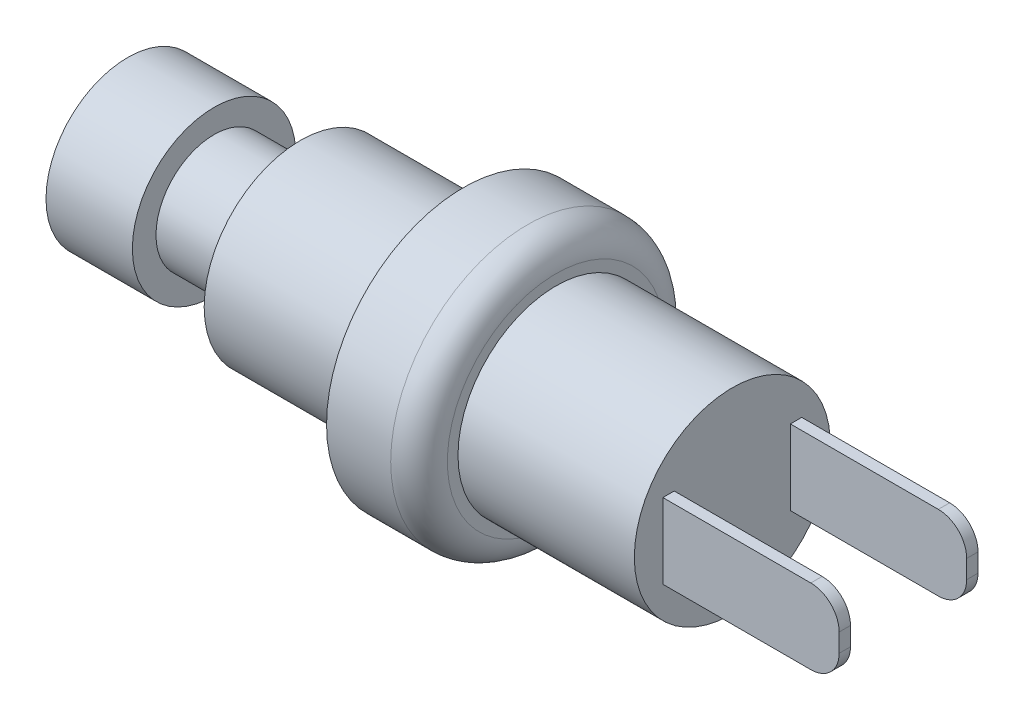
SolidWorks part; units mm, degrees
ref_plane "Front Plane" through (0, 0, 0) normal (0, 0, 1) x (1, 0, 0)
ref_plane "Top Plane" through (0, 0, 0) normal (0, 1, 0) x (1, 0, 0)
ref_plane "Right Plane" through (0, 0, 0) normal (1, 0, 0) x (0, 0, -1)
sketch "Sketch1" plane through (0, 0, 0) normal (0, 0, 1) x (1, 0, 0)
  line L0 (0, 0) -> (23.4906, 0) construction
  line L1 (3.7675, 0) -> (3.7675, 2.883)
  line L2 (3.7675, 2.883) -> (6.8155, 2.883)
  line L3 (6.8155, 2.883) -> (6.8155, 2.05)
  line L4 (6.8155, 2.05) -> (9.8635, 2.05)
  line L5 (9.8635, 2.05) -> (9.8635, 3.397)
  line L6 (9.8635, 3.397) -> (15.6165, 3.397)
  line L7 (15.6165, 3.397) -> (15.6165, 4.832)
  line L8 (15.6165, 4.832) -> (18.8805, 4.832)
  line L9 (18.8805, 4.832) -> (18.8805, 3.4579)
  line L10 (18.8805, 3.4579) -> (25.1035, 3.4579)
  line L11 (25.1035, 3.4579) -> (25.1035, 0)
  line L12 (25.1035, 0) -> (3.7675, 0)
  point P15 (9.8635, 2.7235)
  dimension "D1" = 6.096
  dimension "D2" = 2.883
  dimension "D3" = 5.753
  dimension "D4" = 3.264
  dimension "D5" = 6.223
  dimension "D6" = 4.832
  dimension "D7" = 3.397
revolve "Revolve1" add sketch "Sketch1" angle 360 about L0
fillet "Fillet1" radius 1 1 edges at (18.8805, 0, 4.832)
sketch "Sketch2" plane through (25.1035, 0, 0) normal (1, 0, 0) x (0, 0, -1)
  line L0 (-2.45, 1.325) -> (-2.45, -1.325)
  line L1 (-2.45, -1.325) -> (2.45, -1.325)
  line L2 (2.45, -1.325) -> (2.45, 1.325)
  line L3 (2.45, 1.325) -> (-2.45, 1.325)
  line L4 (-2.45, 1.325) -> (-2.05, 1.325)
  line L5 (-2.05, 1.325) -> (-2.05, -1.325)
  line L6 (2.45, 1.325) -> (2.05, 1.325)
  line L7 (2.05, 1.325) -> (2.05, -1.325)
  point P4 (0, 1.325)
  point P6 (-2.45, 0)
  dimension "D1" = 4.9
  dimension "D2" = 2.65
extrude "Boss-Extrude1" add sketch "Sketch2" along normal blind 6.22 contours L5 L3 L0 L1 | L3 L7 L1 L2
fillet "Fillet2" radius 1 4 edges at (31.3235, -1.325, -2.25) (31.3235, 1.325, -2.25) (31.3235, -1.325, 2.25) (31.3235, 1.325, 2.25)
